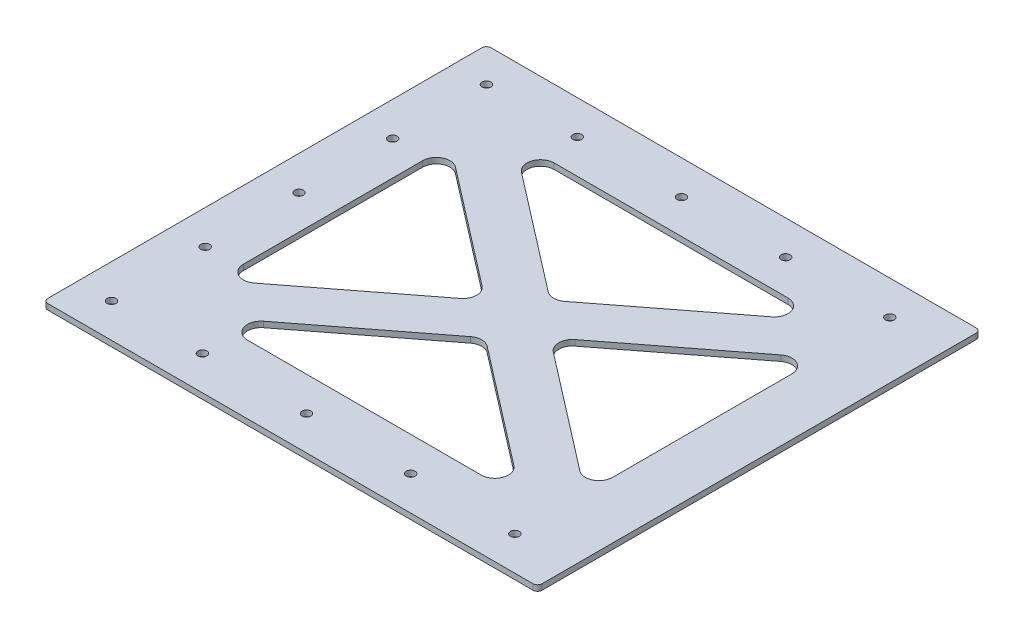
SolidWorks part; units mm, degrees
material "6061 Alloy"
ref_plane "Front Plane" through (0, 0, 0) normal (0, 0, 1) x (1, 0, 0)
ref_plane "Top Plane" through (0, 0, 0) normal (0, 1, 0) x (1, 0, 0)
ref_plane "Right Plane" through (0, 0, 0) normal (1, 0, 0) x (0, 0, -1)
sketch "Sketch1" plane through (0, 0, 0) normal (0, 1, 0) x (1, 0, 0)
  line L1 (0, 0) -> (276.225, 0)
  line L2 (0, 0) -> (0, 247.65)
  line L3 (0, 247.65) -> (276.225, 247.65)
  line L4 (276.225, 0) -> (276.225, 247.65)
  dimension "D1" = 276.225
  dimension "D2" = 247.65
extrude "Boss-Extrude1" add sketch "Sketch1" along normal blind 3.175
sketch "Sketch2" plane through (0, 3.175, 0) normal (0, 1, 0) x (1, 0, 0)
  line L0 (244.475, 209.55) -> (38.1, 209.55) construction
  line L1 (276.225, 0) -> (276.225, 247.65) construction
  line L2 (38.1, 209.55) -> (38.1, 38.1) construction
  line L3 (38.1, 38.1) -> (244.475, 38.1) construction
  line L4 (0, 0) -> (276.225, 0) construction
  line L5 (0, 247.65) -> (0, 0) construction
  line L6 (276.225, 247.65) -> (0, 247.65) construction
  line L7 (38.1, 58.2136) -> (123.1777, 123.825)
  line L8 (123.1777, 123.825) -> (38.1, 189.4364)
  line L9 (38.1, 189.4364) -> (38.1, 58.2136)
  line L13 (53.6115, 209.55) -> (141.2875, 141.9348)
  line L14 (141.2875, 141.9348) -> (228.9635, 209.55)
  line L15 (228.9635, 209.55) -> (53.6115, 209.55)
  line L19 (276.225, 123.825) -> (0, 123.825) construction
  line L20 (141.2875, 209.55) -> (141.2875, 38.1) construction
  line L21 (159.3973, 123.825) -> (244.475, 189.4364)
  line L22 (244.475, 58.2136) -> (159.3973, 123.825)
  line L23 (244.475, 189.4364) -> (244.475, 58.2136)
  line L24 (141.2875, 105.7152) -> (228.9635, 38.1)
  line L25 (53.6115, 38.1) -> (141.2875, 105.7152)
  line L26 (228.9635, 38.1) -> (53.6115, 38.1)
  line L27 (53.6115, 209.55) -> (38.1, 189.4364) construction
  line L28 (123.1777, 123.825) -> (159.3973, 123.825) construction
  line L29 (141.2875, 141.9348) -> (141.2875, 105.7152) construction
  dimension "D1" = 38.1
  dimension "D2" = 38.1
  dimension "D3" = 38.1
  dimension "D4" = 31.75
  dimension "D5" = 25.4
extrude "Cut-Extrude1" cut sketch "Sketch2" against normal through all
hole_wizard "#10 (0.1935) Diameter Hole1" positions "Sketch3" profile "Sketch4" hole size "#10" standard "ANSI Inch" end condition through all
sketch "Sketch3" plane through (0, 3.175, 0) normal (0, 1, 0) x (1, 0, 0)
  line L0 (38.1, 38.1) -> (0, 38.1) construction
  line L1 (0, 247.65) -> (0, 0) construction
  line L2 (19.05, 38.1) -> (19.05, 247.65) construction
  line L3 (276.225, 247.65) -> (0, 247.65) construction
  line L4 (38.1, 209.55) -> (38.1, 247.65) construction
  line L5 (38.1, 228.6) -> (276.225, 228.6) construction
  line L6 (276.225, 0) -> (276.225, 247.65) construction
  line L7 (276.225, 123.825) -> (0, 123.825) construction
  line L8 (276.225, 0) -> (276.225, 247.65) construction
  line L9 (38.1, 38.1) -> (38.1, 0) construction
  line L10 (0, 0) -> (276.225, 0) construction
  line L11 (38.1, 19.05) -> (276.225, 19.05) construction
  point P28 (69.85, 228.6)
  point P47 (19.05, 228.6)
  point P54 (19.05, 176.2125)
  point P55 (19.05, 123.825)
  point P56 (19.05, 71.4375)
  point P57 (19.05, 19.05)
  point P78 (128.0583, 228.6)
  point P79 (186.2667, 228.6)
  point P80 (244.475, 228.6)
  point P84 (244.475, 19.05)
  point P85 (186.2667, 19.05)
  point P86 (128.0583, 19.05)
  point P87 (69.85, 19.05)
  dimension "D3" = 31.75
  dimension "D4" = 31.75
  dimension "D1" = 5
  dimension "D2" = 4
sketch "Sketch4" plane through (69.85, 3.175, -19.05) normal (1, 0, 0) x (0, 0, 1)
  line L0 (0, 0) -> (0, 3.175)
  line L1 (0, 3.175) -> (2.4574, 3.175)
  line L2 (2.4574, 3.175) -> (2.4574, 0)
  line L5 (2.4574, 0) -> (0, 0)
  line L11 (0, -6.35) -> (0, 107.95) construction
  dimension "Thru Hole Dia." = 4.9149
  dimension "Thru Hole Depth" = 3.175
fillet "Fillet1" radius 7.62 12 edges at (38.1, 1.5875, -189.4364) (123.1777, 1.5875, -123.825) (38.1, 1.5875, -58.2136) (159.3973, 1.5875, -123.825) (244.475, 1.5875, -189.4364) (244.475, 1.5875, -58.2136) (228.9635, 1.5875, -209.55) (141.2875, 1.5875, -141.9348) (53.6115, 1.5875, -209.55) (228.9635, 1.5875, -38.1) (53.6115, 1.5875, -38.1) (141.2875, 1.5875, -105.7152)
fillet "Fillet2" radius 2.54 4 edges at (0, 1.5875, -247.65) (276.225, 1.5875, -247.65) (276.225, 1.5875, 0) (0, 1.5875, 0)
